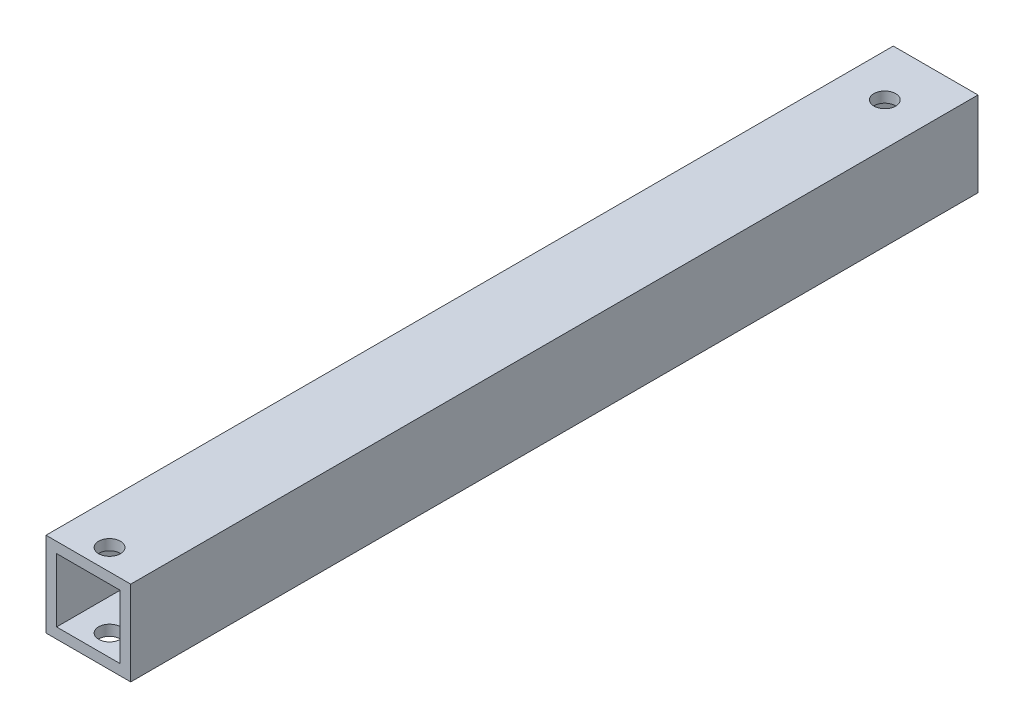
SolidWorks part; units mm, degrees
material "1060 Alloy"
ref_plane "Front Plane" through (0, 0, 0) normal (0, 0, 1) x (1, 0, 0)
ref_plane "Top Plane" through (0, 0, 0) normal (0, 1, 0) x (1, 0, 0)
ref_plane "Right Plane" through (0, 0, 0) normal (1, 0, 0) x (0, 0, -1)
sketch "Sketch2" plane through (0, 0, 0) normal (0, 0, 1) x (1, 0, 0)
  line L1 (12.7, -12.7) -> (-12.7, -12.7)
  line L2 (12.7, -12.7) -> (12.7, 12.7)
  line L3 (12.7, 12.7) -> (-12.7, 12.7)
  line L4 (-12.7, -12.7) -> (-12.7, 12.7)
  line L5 (12.7, -12.7) -> (-12.7, 12.7) construction
  line L6 (12.7, 12.7) -> (-12.7, -12.7) construction
  point P0 (0, 0)
  dimension "D1" = 25.4
extrude "Boss-Extrude1" add sketch "Sketch2" along normal blind 254 contours L4 L3 L2 L1
sketch "Sketch4" plane through (0, 0, 0) normal (0, 0, 1) x (1, 0, 0)
  line L0 (12.7, -12.7) -> (12.7, 12.7) construction
  line L1 (-9.525, -9.525) -> (9.525, -9.525)
  line L2 (-9.525, -9.525) -> (-9.525, 9.525)
  line L3 (-9.525, 9.525) -> (9.525, 9.525)
  line L4 (9.525, -9.525) -> (9.525, 9.525)
  line L5 (-9.525, -9.525) -> (9.525, 9.525) construction
  line L6 (-9.525, 9.525) -> (9.525, -9.525) construction
  line L7 (12.7, 12.7) -> (-12.7, 12.7) construction
  point P0 (0, 0)
  dimension "D1" = 3.175
  dimension "D2" = 3.175
extrude "Cut-Extrude1" cut sketch "Sketch4" along normal through all
sketch "Sketch5" plane through (0, 12.7, 0) normal (0, 1, 0) x (1, 0, 0)
  line L2 (12.7, 0) -> (-12.7, 0) construction
  circle A0 centre (0, -15.24) radius 3.2639
  point P4 (0, 0)
  dimension "D1" = 6.5278
  dimension "D2" = 15.24
extrude "Cut-Extrude2" cut sketch "Sketch5" against normal blind 304.8 contours A0
sketch "Sketch6" plane through (0, 12.7, 0) normal (0, 1, 0) x (1, 0, 0)
  line L0 (12.7, -254) -> (-12.7, -254) construction
  circle A0 centre (0, -247.65) radius 3.2639
  point P4 (0, -254)
  dimension "D1" = 6.5278
  dimension "D2" = 6.35
extrude "Cut-Extrude3" cut sketch "Sketch6" against normal through all
